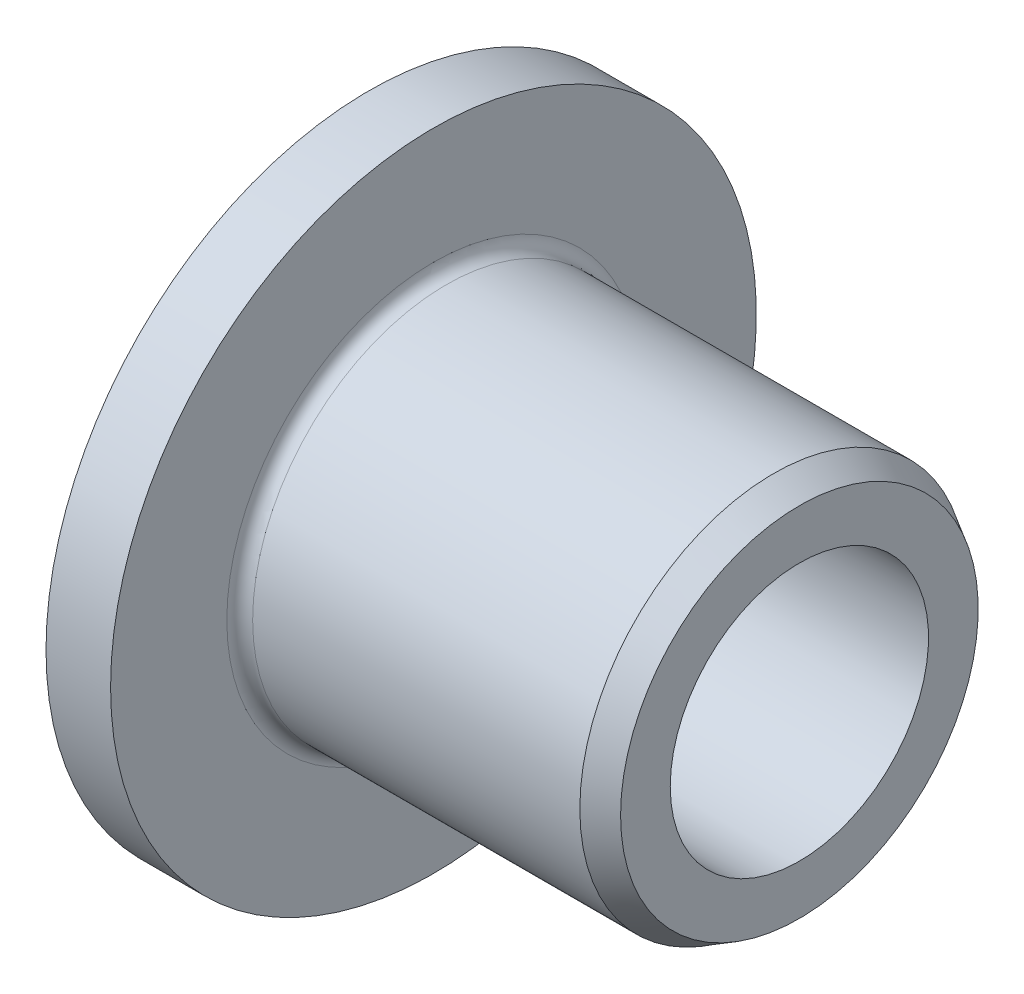
SolidWorks part; units mm, degrees
ref_plane "Front Plane" through (0, 0, 0) normal (0, 0, 1) x (1, 0, 0)
ref_plane "Top Plane" through (0, 0, 0) normal (0, 1, 0) x (1, 0, 0)
ref_plane "Right Plane" through (0, 0, 0) normal (1, 0, 0) x (0, 0, -1)
sketch "Sketch1" plane through (0, 0, 0) normal (0, 0, 1) x (1, 0, 0)
  line L0 (-2.5, -3.75) -> (-2.5, 3.75) construction
  line L1 (-2.5, 3.75) -> (-1.75, 3.75) construction
  line L2 (-1.75, 3.75) -> (-1.75, 2.25) construction
  line L3 (-1.75, 2.25) -> (2.5, 2.25) construction
  line L4 (2.5, 2.25) -> (2.5, 1.5) construction
  line L5 (2.5, 1.5) -> (-2.5, 1.5) construction
  line L6 (-2.5, -3.75) -> (-1.75, -3.75) construction
  line L7 (-1.75, -3.75) -> (-1.75, -2.25) construction
  line L8 (-1.75, -2.25) -> (2.5, -2.25) construction
  line L9 (2.5, -2.25) -> (2.5, -1.5) construction
  line L10 (2.5, -1.5) -> (-2.5, -1.5) construction
  line L11 (2.5, 1.5) -> (2.5, -1.5) construction
  line L12 (-2.5, 0) -> (2.5, 0) construction
  line L13 (2.2, 2.25) -> (2.5, 2.0768) construction
  arc A0 (-1.75, 2.4) -> (-1.6, 2.25) centre (-1.6, 2.4) ccw construction
  dimension "r" = 0.15
  dimension "Flange OD | d3" = 7.5
  dimension "Length | b1" = 5
  dimension "OD | d2" = 4.5
  dimension "ID | d1" = 3
  dimension "Flange Thickness | b2" = 0.75
  dimension "Chamfer Angle" = 30
  dimension "f" = 0.3
sketch "Sketch2" plane through (0, 0, 0) normal (1, 0, 0) x (0, 0, -1)
  line L0 (0, -3.75) -> (0, 3.75) construction
  circle A3 centre (0, 0) radius 1.4938 construction
  circle A4 centre (0, 0) radius 2.253 construction
  dimension "For Shaft Diameter" = 2.9875
  dimension "For Housing ID" = 4.506
sketch "Sketch3" plane through (0, 0, 0) normal (0, 0, 1) x (1, 0, 0)
  line L0 (-1.6, 2.25) -> (2.2, 2.25)
  line L1 (2.2, 2.25) -> (2.5, 2.0768)
  line L2 (2.5, 2.0768) -> (2.5, 1.5)
  line L3 (2.5, 1.5) -> (-2.5, 1.5)
  line L4 (-2.5, 1.5) -> (-2.5, 3.75)
  line L5 (-2.5, 3.75) -> (-1.75, 3.75)
  line L6 (-1.75, 3.75) -> (-1.75, 2.4)
  arc A0 (-1.75, 2.4) -> (-1.6, 2.25) centre (-1.6, 2.4) ccw
revolve "Revolve1" add sketch "Sketch3" angle 360 about L12
equation "\"r@Sketch1\"=\"f@Sketch1\" / 2"
